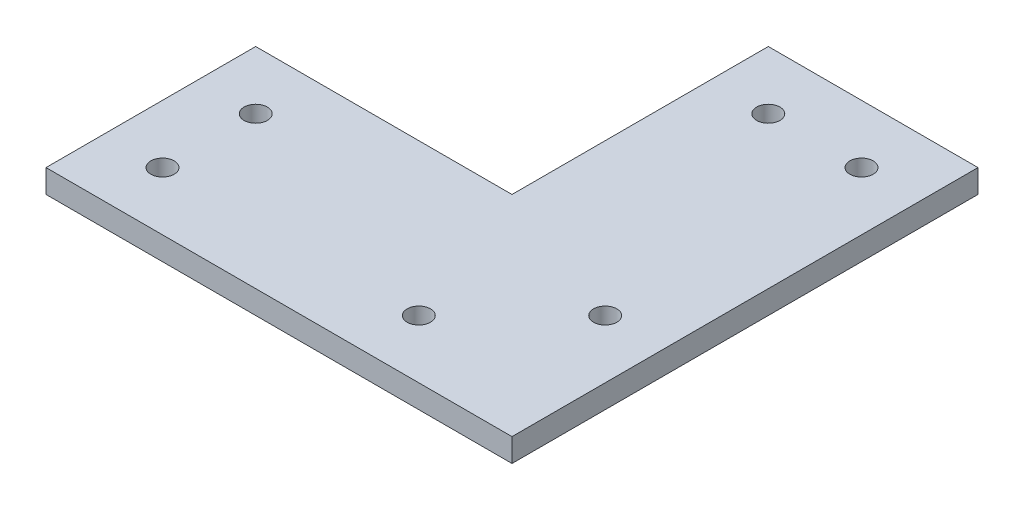
SolidWorks part; units mm, degrees
ref_plane "Front Plane" through (0, 0, 0) normal (0, 0, 1) x (1, 0, 0)
ref_plane "Top Plane" through (0, 0, 0) normal (0, 1, 0) x (1, 0, 0)
ref_plane "Right Plane" through (0, 0, 0) normal (1, 0, 0) x (0, 0, -1)
sketch "Sketch1" plane through (0, 0, 0) normal (0, 1, 0) x (1, 0, 0)
  line L0 (0, 0) -> (0, 28.575)
  line L1 (0, 0) -> (63.5, 0)
  line L4 (63.5, 0) -> (63.5, 63.5)
  line L5 (0, 28.575) -> (34.925, 28.575)
  line L6 (34.925, 28.575) -> (34.925, 63.5)
  line L7 (34.925, 63.5) -> (63.5, 63.5)
  circle A0 centre (7.9375, 20.6375) radius 1.5875
  circle A1 centre (7.9375, 7.9375) radius 1.5875
  circle A2 centre (42.8625, 7.9375) radius 1.5875
  circle A3 centre (55.5625, 20.6375) radius 1.5875
  circle A4 centre (55.5625, 55.5625) radius 1.5875
  circle A5 centre (42.8625, 55.5625) radius 1.5875
  dimension "D1" = 3.175
  dimension "D2" = 28.575
  dimension "D3" = 63.5
  dimension "D4" = 7.9375
  dimension "D5" = 7.9375
  dimension "D12" = 7.9375
  dimension "D11" = 7.9375
  dimension "D8" = 34.925
  dimension "D9" = 34.925
  dimension "D7" = 20.6375
  dimension "D10" = 7.9375
  dimension "D6" = 12.7
extrude "Boss-Extrude1" add sketch "Sketch1" along normal blind 3.175
equation "\"TopCBWidth\"= \"TopRailWidth\" - \"RailThickness\"'Equals 28.575"
equation "\"TopCBLength\"= \"TopRailWidth\" * 2'Equals 63.5"
equation "\"RailThickness\"= .125in'Spec"
equation "\"TopCBHeight\"= \"RailThickness\""
equation "\"TopRailWidth\"= 1.25in"
equation "\"HoleOffsetFromEdge\"= \"RailThickness\" * 2.5"
equation "\"D1@Boss-Extrude1\"=\"TopCBHeight\""
equation "\"D3@Sketch1\"=\"TopCBLength\" "
equation "\"D2@Sketch1\"=\"TopRailWidth\" - \"RailThickness\""
equation "\"FasteningHoleDiameter\"= .125in"
equation "\"TopHoleX1FromEdge\"= \"TopCBWidth\" - \"HoleOffsetFromEdge\"'Equals 20.6375"
equation "\"TopHoleX2FromX1\"= \"TopCBLength\" - \"TopHoleX1FromEdge\" - \"HoleOffsetFromEdge\"'Equals 34.925"
equation "\"TopHoleY1FromEdge\"= \"HoleOffsetFromEdge\""
equation "\"TopHoleY2FromY1\"= \"TopCBWidth\" - \"TopHoleY1FromEdge\" - \"HoleOffsetFromEdge\"'Equals 12.7"
equation "\"D1@Sketch1\"=\"FasteningHoleDiameter\""
equation "\"D5@Sketch1\"=\"TopHoleY1FromEdge\""
equation "\"D4@Sketch1\"=\"TopHoleY1FromEdge\""
equation "\"D7@Sketch1\"=\"TopHoleX1FromEdge\""
equation "\"D9@Sketch1\"=\"TopHoleX2FromX1\""
equation "\"D8@Sketch1\"=\"TopHoleX2FromX1\""
equation "\"D6@Sketch1\"=\"TopHoleY2FromY1\""
